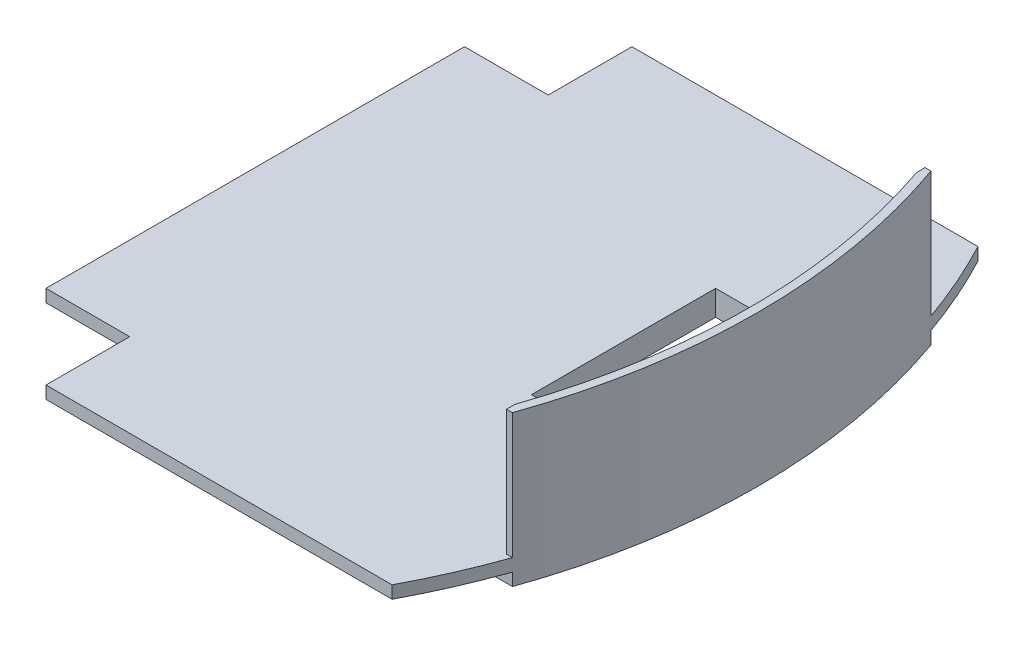
SolidWorks part; units mm, degrees
ref_plane "Front Plane" through (0, 0, 0) normal (0, 0, 1) x (1, 0, 0)
ref_plane "Top Plane" through (0, 0, 0) normal (0, 1, 0) x (1, 0, 0)
ref_plane "Right Plane" through (0, 0, 0) normal (1, 0, 0) x (0, 0, -1)
sketch "Sketch1" plane through (0, 0, 0) normal (0, 1, 0) x (1, 0, 0)
  line L0 (29.9711, -50) -> (29.9711, 50)
  line L5 (29.9711, 50) -> (141.4214, 50)
  line L8 (29.9711, -50) -> (141.4214, -50)
  line L9 (141.4214, -50) -> (29.9711, -50)
  line L10 (49.9711, -70) -> (132.665, -70)
  line L11 (49.9711, 70) -> (132.665, 70)
  line L12 (29.9711, -0.5884) -> (29.9711, -50)
  line L13 (49.9711, -0.9811) -> (49.9711, -70)
  line L14 (29.9711, -0.5884) -> (29.9711, 50)
  line L15 (49.9711, -0.9811) -> (49.9711, 70)
  arc A0 (132.665, -70) -> (132.665, 70) centre (0, 0) ccw
  point P11 (0, -70)
  point P15 (49.9711, -0.9811)
  point P16 (29.9711, -0.5884)
  dimension "D1" = 300
  dimension "D7" = 20
extrude "Boss-Extrude1" add sketch "Sketch1" along normal blind 6 contours L9 A0 L5 L15 L13 | L10 A0 L9 L13 | L13 L15 L5 L0 L8 | L5 A0 L11 L15
sketch "Sketch3" plane through (0, 0, 0) normal (0, -1, 0) x (1, 0, 0)
  line L0 (49.9711, 50) -> (49.9711, -50)
  line L1 (49.9711, -50) -> (29.9711, -50)
  line L2 (29.9711, -50) -> (29.9711, 50)
  line L3 (29.9711, 50) -> (49.9711, 50)
  line L4 (132.665, 70) -> (66.2609, 70)
  line L5 (49.9711, 70) -> (132.665, 70) construction
  line L6 (49.9711, 70) -> (49.9711, 50)
  line L7 (49.9711, 50) -> (141.4214, 50)
  line L8 (132.665, -70) -> (49.9711, -70)
  line L9 (49.9711, -70) -> (49.9711, -50)
  line L10 (49.9711, -50) -> (141.4214, -50)
  arc A0 (141.4214, 50) -> (132.665, 70) centre (0, 0) ccw
  arc A1 (132.665, -70) -> (132.665, 70) centre (0, 0) ccw construction
  arc A2 (141.4214, -50) -> (132.665, -70) centre (0, 0) cw
  line M1 (49.9711, 50) -> (29.9711, 50)
  line M2 (29.9711, 50) -> (29.9711, -50)
  line M3 (29.9711, -50) -> (49.9711, -50)
  line M4 (49.9711, -50) -> (49.9711, -70)
  line M5 (49.9711, -70) -> (132.665, -70)
  arc M6 (132.665, -70) -> (132.665, 70) centre (0, 0) ccw
  line M7 (132.665, 70) -> (49.9711, 70)
  line M8 (49.9711, 70) -> (49.9711, 50)
extrude "Cut-Extrude1" cut sketch "Sketch3" against normal blind 3 contours L0 M1 M2 M3 | L7 M8 M6 M7 | L10 M4 M5 M6
sketch "Sketch4" plane through (0, 6, 0) normal (0, 1, 0) x (-1, 0, 0)
  line L0 (-49.9711, -50) -> (-49.9711, 50)
  line L1 (-49.9711, 50) -> (-141.4214, 50)
  line L2 (-49.9711, -50) -> (-141.4214, -50)
  arc A0 (-132.665, 70) -> (-132.665, -70) centre (0, 0) ccw construction
  arc A1 (-141.4214, -50) -> (-141.4214, 50) centre (0, 0) cw
  arc M8 (-132.665, 70) -> (-132.665, -70) centre (0, 0) ccw
extrude "Boss-Extrude2" add sketch "Sketch4" along normal blind 30 contours L2 L0 L1 M8
shell "Shell1" thickness 2
sketch "Sketch5" plane through (49.9711, 0, 0) normal (-1, 0, 0) x (0, 0, 1)
  line L0 (-48, 36) -> (-48, 6)
  line L1 (-48, 36) -> (-48, 2) construction
  line L2 (50, 6) -> (-50, 6) construction
  line L3 (-48, 6) -> (48, 6)
  line L4 (48, 36) -> (48, 2) construction
  line L5 (48, 6) -> (48, 36)
  line L6 (48, 36) -> (-48, 36)
  line M1 (-50, 6) -> (50, 6)
  line M3 (50, 36) -> (-50, 36)
extrude "Cut-Extrude2" cut sketch "Sketch5" against normal blind 2 contours L5 L0 M1 M3
sketch "Sketch6" plane through (0, 0, 0) normal (0, -1, 0) x (1, 0, 0)
  line L0 (141.4214, 50) -> (49.9711, 50)
  line L1 (49.9711, 50) -> (49.9711, -50)
  line L2 (49.9711, -50) -> (141.4214, -50)
  arc A0 (141.4214, 50) -> (141.4214, -50) centre (0, 0) cw
extrude "Boss-Extrude3" add sketch "Sketch6" against normal blind 6
sketch "Sketch7" plane through (0, 0, 0) normal (0, -1, 0) x (1, 0, 0)
  line L0 (49.9711, 50) -> (49.9711, -50) construction
  line L1 (109.9711, 14) -> (130.9711, 14)
  line L2 (109.9711, 14) -> (109.9711, -30)
  line L3 (109.9711, -30) -> (130.9711, -30)
  line L4 (130.9711, 14) -> (130.9711, -30)
  line L5 (49.9711, -50) -> (141.4214, -50) construction
  point P6 (0, 0)
  dimension "D1" = 44
  dimension "D2" = 21
  dimension "D3" = 60
  dimension "D4" = 20
extrude "Cut-Extrude3" cut sketch "Sketch7" against normal blind 6 contours L4 L1 L2 L3
sketch "Sketch8" plane through (0, 0, 50) normal (0, 0, 1) x (1, 0, 0)
  line L0 (49.9711, 6) -> (49.9711, 36)
  line L1 (49.9711, 36) -> (140, 36)
  line L2 (140, 36) -> (140, 6)
  line L3 (140, 6) -> (49.9711, 6)
extrude "Cut-Extrude4" cut sketch "Sketch8" against normal through all
